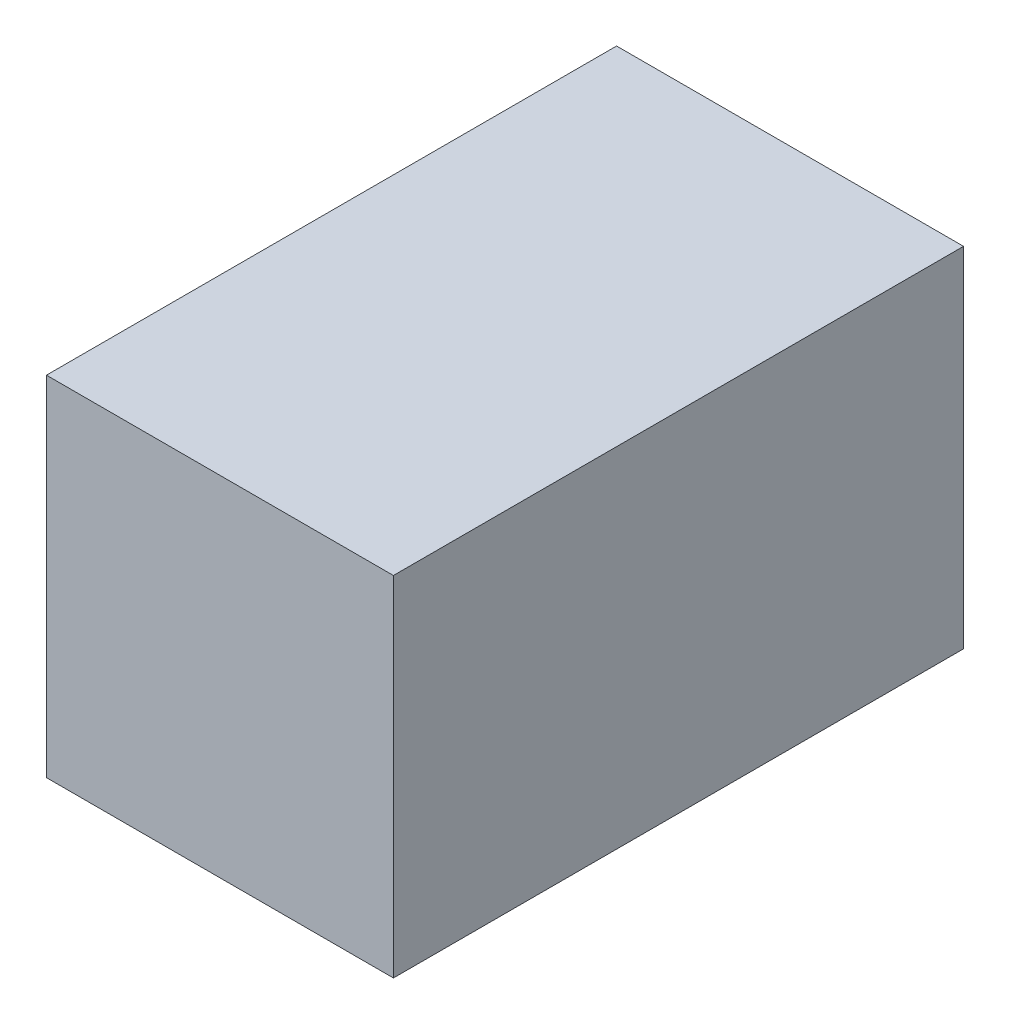
SolidWorks part; units mm, degrees
ref_plane "Front Plane" through (0, 0, 0) normal (0, 0, 1) x (1, 0, 0)
ref_plane "Top Plane" through (0, 0, 0) normal (0, 1, 0) x (1, 0, 0)
ref_plane "Right Plane" through (0, 0, 0) normal (1, 0, 0) x (0, 0, -1)
sketch "Sketch1" plane through (0, 0, 0) normal (0, 0, 1) x (1, 0, 0)
  line L1 (-106.5, -107) -> (106.5, -107)
  line L2 (-106.5, -107) -> (-106.5, 107)
  line L3 (-106.5, 107) -> (106.5, 107)
  line L4 (106.5, -107) -> (106.5, 107)
  line L5 (-106.5, -107) -> (106.5, 107) construction
  line L6 (-106.5, 107) -> (106.5, -107) construction
  point P0 (0, 0)
  dimension "D1" = 214
  dimension "D2" = 213
extrude "Boss-Extrude1" add sketch "Sketch1" along normal blind 350
